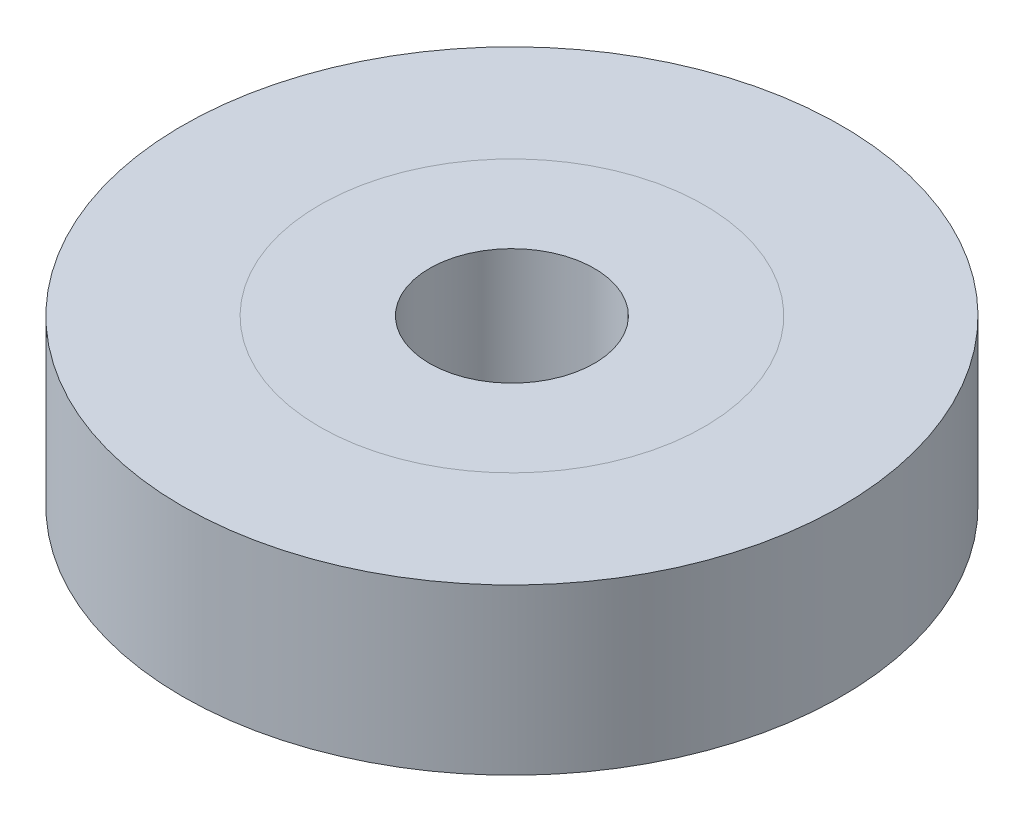
SolidWorks part; units mm, degrees
ref_plane "前视基准面" through (0, 0, 0) normal (0, 0, 1) x (1, 0, 0)
ref_plane "上视基准面" through (0, 0, 0) normal (0, 1, 0) x (1, 0, 0)
ref_plane "右视基准面" through (0, 0, 0) normal (1, 0, 0) x (0, 0, -1)
sketch "草图1" plane through (0, 0, 0) normal (0, 1, 0) x (1, 0, 0)
  circle A0 centre (0, 0) radius 1.5
  circle A1 centre (0, 0) radius 3.5
  dimension "D1" = 3
  dimension "D2" = 7
extrude "凸台-拉伸1" add sketch "草图1" along normal mid plane 3
sketch "草图2" plane through (0, 0, 0) normal (0, 1, 0) x (1, 0, 0)
  circle A0 centre (0, 0) radius 6
  circle A1 centre (0, 0) radius 3.5 construction
  circle A2 centre (0, 0) radius 3.5
  dimension "D1" = 12
extrude "凸台-拉伸2" add sketch "草图2" along normal mid plane 3 separate body
sketch "草图3" plane through (0, 1.5, 0) normal (0, 1, 0) x (1, 0, 0)
  circle A2 centre (0, 0) radius 5.5
  circle A3 centre (0, 0) radius 5.5 construction
  text T0 "https://item.taobao.com/item.htm?spm=a1z10.3-c.w4002-15226105362.15.e702319dne47Ao&id=538767949710" font "黑体" height 0.5
  dimension "D1" = 0.5
extrude "切除-拉伸1" [suppressed] cut sketch "草图3" against normal blind 0.1
